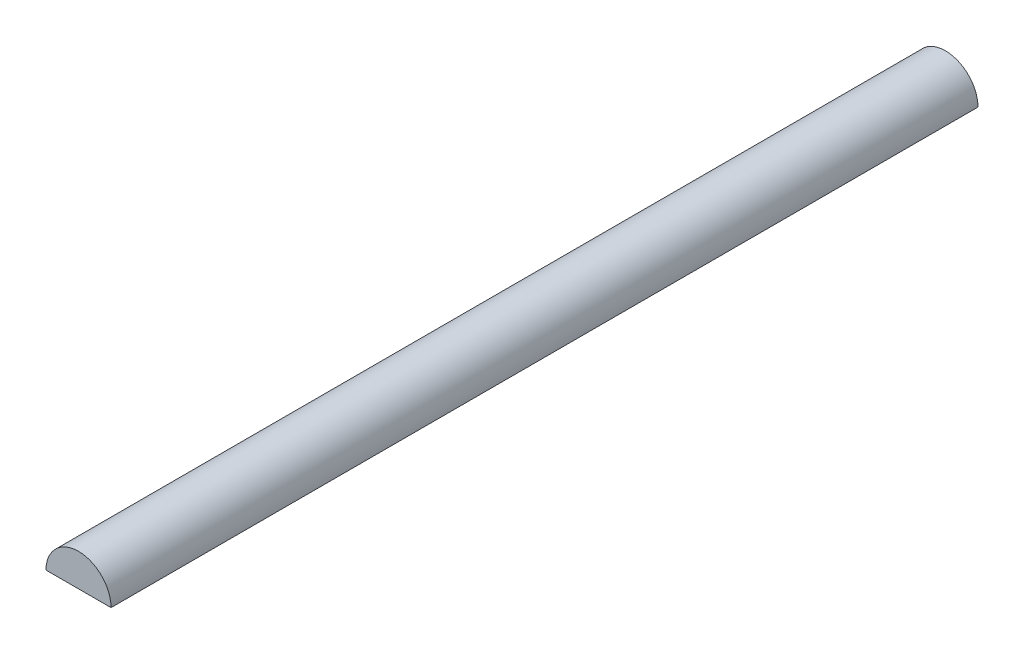
SolidWorks part; units mm, degrees
ref_plane "Front Plane" through (0, 0, 0) normal (0, 0, 1) x (1, 0, 0)
ref_plane "Top Plane" through (0, 0, 0) normal (0, 1, 0) x (1, 0, 0)
ref_plane "Right Plane" through (0, 0, 0) normal (1, 0, 0) x (0, 0, -1)
sketch "Sketch1" plane through (0, 0, 0) normal (0, 0, 1) x (1, 0, 0)
  circle A0 centre (0, 0) radius 0.75
  dimension "D1" = 1.5
extrude "Boss-Extrude1" add sketch "Sketch1" along normal blind 20
sketch "Sketch2" plane through (0, 0, 0) normal (0, 1, 0) x (1, 0, 0)
  line L1 (-6.9128, 5.0074) -> (6.9128, 5.0074)
  line L2 (-6.9128, 5.0074) -> (-6.9128, -24.4076)
  line L3 (-6.9128, -24.4076) -> (6.9128, -24.4076)
  line L4 (6.9128, 5.0074) -> (6.9128, -24.4076)
  line L5 (-6.9128, 5.0074) -> (6.9128, -24.4076) construction
  line L6 (-6.9128, -24.4076) -> (6.9128, 5.0074) construction
  point P0 (0, -9.7001)
extrude "Cut-Extrude1" cut sketch "Sketch2" against normal blind 20
